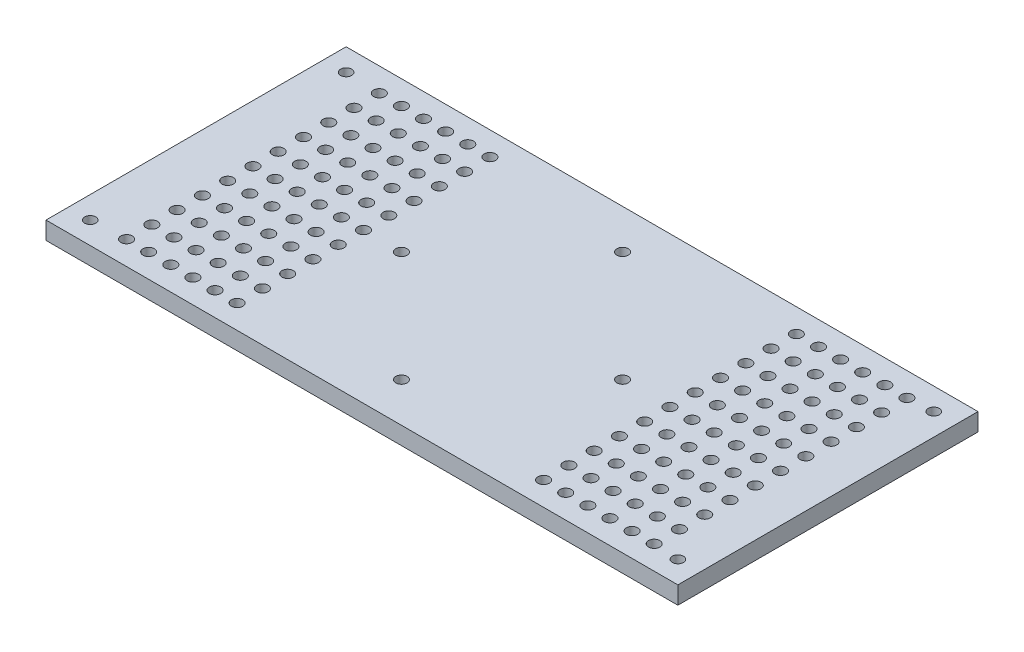
SolidWorks part; units mm, degrees
ref_plane "Front Plane" through (0, 0, 0) normal (0, 0, 1) x (1, 0, 0)
ref_plane "Top Plane" through (0, 0, 0) normal (0, 1, 0) x (1, 0, 0)
ref_plane "Right Plane" through (0, 0, 0) normal (1, 0, 0) x (0, 0, -1)
sketch "Sketch1" plane through (0, 0, 0) normal (0, 1, 0) x (1, 0, 0)
  line L1 (-93.9861, 51.2286) -> (106.0139, 51.2286)
  line L2 (-93.9861, 51.2286) -> (-93.9861, -43.7714)
  line L3 (-93.9861, -43.7714) -> (106.0139, -43.7714)
  line L4 (106.0139, 51.2286) -> (106.0139, -43.7714)
  dimension "D1" = 200
  dimension "D2" = 95
extrude "Boss-Extrude1" add sketch "Sketch1" along normal blind 5.588
sketch "Sketch3" plane through (0, 5.588, 0) normal (0, 1, 0) x (1, 0, 0)
  line L0 (-93.9861, 51.2286) -> (-93.9861, -43.7714) construction
  line L1 (106.0139, 51.2286) -> (-93.9861, 51.2286) construction
  line L2 (-93.9861, -43.7714) -> (106.0139, -43.7714) construction
  line L3 (106.0139, -43.7714) -> (106.0139, 51.2286) construction
  line L4 (-93.9861, 3.7286) -> (106.0139, 3.7286) construction
  line L5 (6.0139, -43.7714) -> (6.0139, 51.2286) construction
  line L6 (-86.9861, -36.7714) -> (-86.9861, 44.2286) construction
  line L7 (-86.9861, 44.2286) -> (99.0139, 44.2286) construction
  line L8 (99.0139, 44.2286) -> (99.0139, -36.7714) construction
  line L9 (99.0139, -36.7714) -> (-86.9861, -36.7714) construction
  line L10 (-28.9861, -31.2714) -> (-28.9861, 38.7286) construction
  line L11 (-28.9861, 38.7286) -> (41.0139, 38.7286) construction
  line L12 (41.0139, 38.7286) -> (41.0139, -31.2714) construction
  line L13 (41.0139, -31.2714) -> (-28.9861, -31.2714) construction
  circle A0 centre (-86.9861, -36.7714) radius 1.75
  circle A1 centre (-86.9861, 44.2286) radius 1.75
  circle A2 centre (99.0139, 44.2286) radius 1.75
  circle A3 centre (99.0139, -36.7714) radius 1.75
  circle A4 centre (-28.9861, 3.7286) radius 1.8
  circle A5 centre (6.0139, 38.7286) radius 1.8
  circle A6 centre (6.0139, -31.2714) radius 1.8
  circle A7 centre (41.0139, 3.7286) radius 1.8
  dimension "D1" = 3.5
  dimension "D5" = 3.6
  dimension "D2" = 186
  dimension "D3" = 81
  dimension "D4" = 70
extrude "Cut-Extrude2" cut sketch "Sketch3" against normal through all
sketch "Sketch4" plane through (0, 5.588, 0) normal (0, 1, 0) x (1, 0, 0)
  line L0 (-93.9861, 51.2286) -> (-93.9861, -43.7714) construction
  line L2 (-93.9861, 3.7286) -> (106.0139, 3.7286) construction
  line L3 (106.0139, -43.7714) -> (106.0139, 51.2286) construction
  circle A0 centre (-75.9861, 43.7286) radius 1.8
  circle A1 centre (56.0139, 43.7286) radius 1.8
  circle A2 centre (-68.9861, 43.7286) radius 1.8
  circle A3 centre (-61.9861, 43.7286) radius 1.8
  circle A4 centre (-54.9861, 43.7286) radius 1.8
  circle A5 centre (-47.9861, 43.7286) radius 1.8
  circle A6 centre (-40.9861, 43.7286) radius 1.8
  circle A7 centre (-68.9861, 35.7286) radius 1.8
  circle A8 centre (-61.9861, 35.7286) radius 1.8
  circle A9 centre (-54.9861, 35.7286) radius 1.8
  circle A10 centre (-47.9861, 35.7286) radius 1.8
  circle A11 centre (-40.9861, 35.7286) radius 1.8
  circle A12 centre (-68.9861, 27.7286) radius 1.8
  circle A13 centre (-61.9861, 27.7286) radius 1.8
  circle A14 centre (-54.9861, 27.7286) radius 1.8
  circle A15 centre (-47.9861, 27.7286) radius 1.8
  circle A16 centre (-40.9861, 27.7286) radius 1.8
  circle A17 centre (-68.9861, 19.7286) radius 1.8
  circle A18 centre (-61.9861, 19.7286) radius 1.8
  circle A19 centre (-54.9861, 19.7286) radius 1.8
  circle A20 centre (-47.9861, 19.7286) radius 1.8
  circle A21 centre (-40.9861, 19.7286) radius 1.8
  circle A22 centre (-68.9861, 11.7286) radius 1.8
  circle A23 centre (-61.9861, 11.7286) radius 1.8
  circle A24 centre (-54.9861, 11.7286) radius 1.8
  circle A25 centre (-47.9861, 11.7286) radius 1.8
  circle A26 centre (-40.9861, 11.7286) radius 1.8
  circle A27 centre (-68.9861, 3.7286) radius 1.8
  circle A28 centre (-61.9861, 3.7286) radius 1.8
  circle A29 centre (-54.9861, 3.7286) radius 1.8
  circle A30 centre (-47.9861, 3.7286) radius 1.8
  circle A31 centre (-40.9861, 3.7286) radius 1.8
  circle A32 centre (-68.9861, -4.2714) radius 1.8
  circle A33 centre (-61.9861, -4.2714) radius 1.8
  circle A34 centre (-54.9861, -4.2714) radius 1.8
  circle A35 centre (-47.9861, -4.2714) radius 1.8
  circle A36 centre (-40.9861, -4.2714) radius 1.8
  circle A37 centre (-68.9861, -12.2714) radius 1.8
  circle A38 centre (-61.9861, -12.2714) radius 1.8
  circle A39 centre (-54.9861, -12.2714) radius 1.8
  circle A40 centre (-47.9861, -12.2714) radius 1.8
  circle A41 centre (-40.9861, -12.2714) radius 1.8
  circle A42 centre (-68.9861, -20.2714) radius 1.8
  circle A43 centre (-61.9861, -20.2714) radius 1.8
  circle A44 centre (-54.9861, -20.2714) radius 1.8
  circle A45 centre (-47.9861, -20.2714) radius 1.8
  circle A46 centre (-40.9861, -20.2714) radius 1.8
  circle A47 centre (-68.9861, -28.2714) radius 1.8
  circle A48 centre (-61.9861, -28.2714) radius 1.8
  circle A49 centre (-54.9861, -28.2714) radius 1.8
  circle A50 centre (-47.9861, -28.2714) radius 1.8
  circle A51 centre (-40.9861, -28.2714) radius 1.8
  circle A52 centre (-68.9861, -36.2714) radius 1.8
  circle A53 centre (-61.9861, -36.2714) radius 1.8
  circle A54 centre (-54.9861, -36.2714) radius 1.8
  circle A55 centre (-47.9861, -36.2714) radius 1.8
  circle A56 centre (-40.9861, -36.2714) radius 1.8
  circle A57 centre (-75.9861, 35.7286) radius 1.8
  circle A58 centre (-75.9861, 27.7286) radius 1.8
  circle A59 centre (-75.9861, 19.7286) radius 1.8
  circle A60 centre (-75.9861, 11.7286) radius 1.8
  circle A61 centre (-75.9861, 3.7286) radius 1.8
  circle A62 centre (-75.9861, -4.2714) radius 1.8
  circle A63 centre (-75.9861, -12.2714) radius 1.8
  circle A64 centre (-75.9861, -20.2714) radius 1.8
  circle A65 centre (-75.9861, -28.2714) radius 1.8
  circle A66 centre (-75.9861, -36.2714) radius 1.8
  circle A67 centre (63.0139, 43.7286) radius 1.8
  circle A68 centre (70.0139, 43.7286) radius 1.8
  circle A69 centre (77.0139, 43.7286) radius 1.8
  circle A70 centre (84.0139, 43.7286) radius 1.8
  circle A71 centre (91.0139, 43.7286) radius 1.8
  circle A72 centre (63.0139, 35.7286) radius 1.8
  circle A73 centre (70.0139, 35.7286) radius 1.8
  circle A74 centre (77.0139, 35.7286) radius 1.8
  circle A75 centre (84.0139, 35.7286) radius 1.8
  circle A76 centre (91.0139, 35.7286) radius 1.8
  circle A77 centre (63.0139, 27.7286) radius 1.8
  circle A78 centre (70.0139, 27.7286) radius 1.8
  circle A79 centre (77.0139, 27.7286) radius 1.8
  circle A80 centre (84.0139, 27.7286) radius 1.8
  circle A81 centre (91.0139, 27.7286) radius 1.8
  circle A82 centre (63.0139, 19.7286) radius 1.8
  circle A83 centre (70.0139, 19.7286) radius 1.8
  circle A84 centre (77.0139, 19.7286) radius 1.8
  circle A85 centre (84.0139, 19.7286) radius 1.8
  circle A86 centre (91.0139, 19.7286) radius 1.8
  circle A87 centre (63.0139, 11.7286) radius 1.8
  circle A88 centre (70.0139, 11.7286) radius 1.8
  circle A89 centre (77.0139, 11.7286) radius 1.8
  circle A90 centre (84.0139, 11.7286) radius 1.8
  circle A91 centre (91.0139, 11.7286) radius 1.8
  circle A92 centre (63.0139, 3.7286) radius 1.8
  circle A93 centre (70.0139, 3.7286) radius 1.8
  circle A94 centre (77.0139, 3.7286) radius 1.8
  circle A95 centre (84.0139, 3.7286) radius 1.8
  circle A96 centre (91.0139, 3.7286) radius 1.8
  circle A97 centre (63.0139, -4.2714) radius 1.8
  circle A98 centre (70.0139, -4.2714) radius 1.8
  circle A99 centre (77.0139, -4.2714) radius 1.8
  circle A100 centre (84.0139, -4.2714) radius 1.8
  circle A101 centre (91.0139, -4.2714) radius 1.8
  circle A102 centre (63.0139, -12.2714) radius 1.8
  circle A103 centre (70.0139, -12.2714) radius 1.8
  circle A104 centre (77.0139, -12.2714) radius 1.8
  circle A105 centre (84.0139, -12.2714) radius 1.8
  circle A106 centre (91.0139, -12.2714) radius 1.8
  circle A107 centre (63.0139, -20.2714) radius 1.8
  circle A108 centre (70.0139, -20.2714) radius 1.8
  circle A109 centre (77.0139, -20.2714) radius 1.8
  circle A110 centre (84.0139, -20.2714) radius 1.8
  circle A111 centre (91.0139, -20.2714) radius 1.8
  circle A112 centre (63.0139, -28.2714) radius 1.8
  circle A113 centre (70.0139, -28.2714) radius 1.8
  circle A114 centre (77.0139, -28.2714) radius 1.8
  circle A115 centre (84.0139, -28.2714) radius 1.8
  circle A116 centre (91.0139, -28.2714) radius 1.8
  circle A117 centre (63.0139, -36.2714) radius 1.8
  circle A118 centre (70.0139, -36.2714) radius 1.8
  circle A119 centre (77.0139, -36.2714) radius 1.8
  circle A120 centre (84.0139, -36.2714) radius 1.8
  circle A121 centre (91.0139, -36.2714) radius 1.8
  circle A122 centre (56.0139, 35.7286) radius 1.8
  circle A123 centre (56.0139, 27.7286) radius 1.8
  circle A124 centre (56.0139, 19.7286) radius 1.8
  circle A125 centre (56.0139, 11.7286) radius 1.8
  circle A126 centre (56.0139, 3.7286) radius 1.8
  circle A127 centre (56.0139, -4.2714) radius 1.8
  circle A128 centre (56.0139, -12.2714) radius 1.8
  circle A129 centre (56.0139, -20.2714) radius 1.8
  circle A130 centre (56.0139, -28.2714) radius 1.8
  circle A131 centre (56.0139, -36.2714) radius 1.8
  dimension "D1" = 3.6
  dimension "D4" = 18
  dimension "D5" = 6
  dimension "D7" = 15
  dimension "D2" = 6
  dimension "D3" = 11
  dimension "D6" = 11
extrude "Cut-Extrude3" cut sketch "Sketch4" against normal through all
